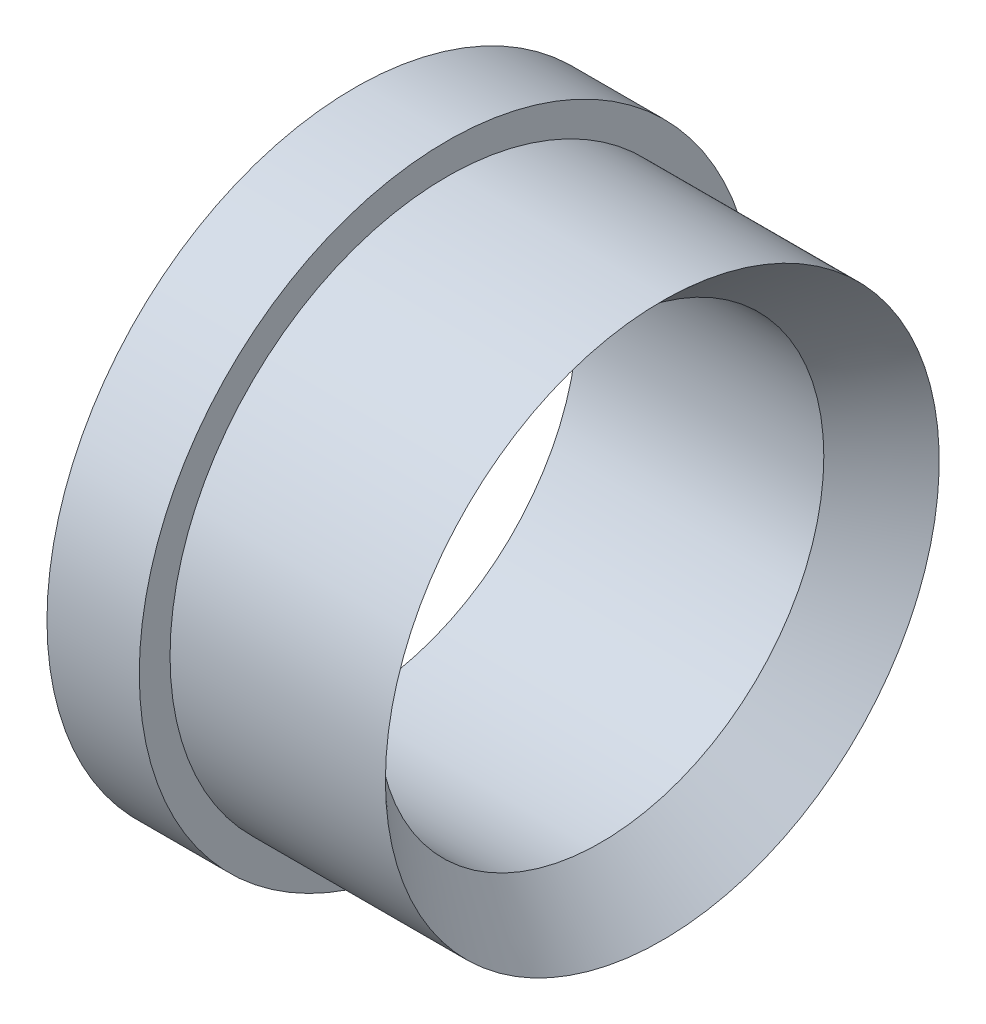
SolidWorks part; units mm, degrees
ref_plane "Спереди" through (0, 0, 0) normal (0, 0, 1) x (1, 0, 0)
ref_plane "Сверху" through (0, 0, 0) normal (0, 1, 0) x (1, 0, 0)
ref_plane "Справа" through (0, 0, 0) normal (1, 0, 0) x (0, 0, -1)
sketch "Эскиз1" plane through (0, 0, 0) normal (0, 0, 1) x (1, 0, 0)
  line L0 (0, 0) -> (12.3956, 0) construction
  line L1 (0, 0) -> (0, 7.25) construction
  line L2 (0, 7.25) -> (8, 7.25)
  line L3 (0, 7.25) -> (0, 10)
  line L4 (0, 10) -> (3, 10)
  line L5 (3, 10) -> (3, 9)
  line L6 (3, 9) -> (10, 9)
  line L7 (10, 9) -> (10, 7.25) construction
  line L8 (10, 9) -> (8, 7.25)
  dimension "D1" = 14.5
  dimension "D2" = 20
  dimension "D3" = 7
  dimension "D4" = 18
  dimension "D5" = 10
  dimension "D6" = 2
revolve "Повернуть1" add sketch "Эскиз1" angle 360 about L0
